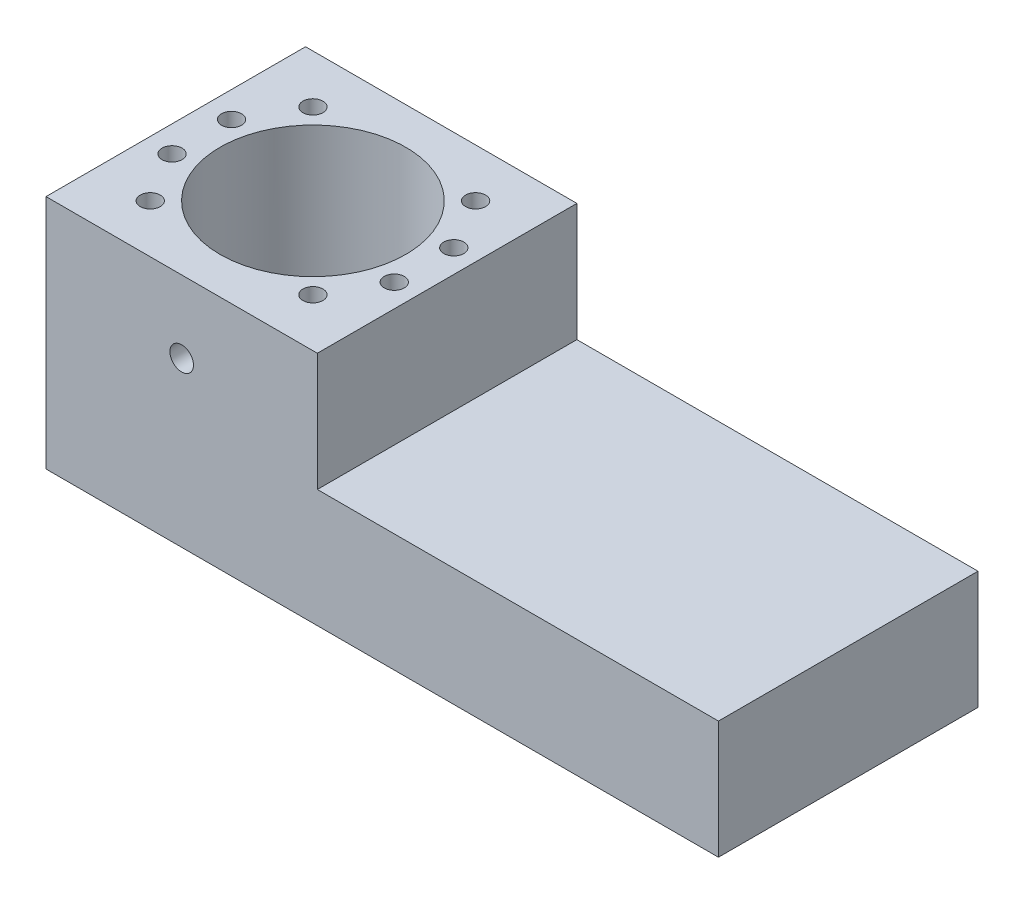
SolidWorks part; units mm, degrees
ref_plane "前视基准面" through (0, 0, 0) normal (0, 0, 1) x (1, 0, 0)
ref_plane "上视基准面" through (0, 0, 0) normal (0, 1, 0) x (1, 0, 0)
ref_plane "右视基准面" through (0, 0, 0) normal (1, 0, 0) x (0, 0, -1)
other "Configuration Table"
sketch "草图2" plane through (0, 0, 0) normal (0, 1, 0) x (1, 0, 0)
  line L1 (0, 0) -> (228, 0)
  line L2 (0, 0) -> (0, 88)
  line L3 (0, 88) -> (228, 88)
  line L4 (228, 0) -> (228, 88)
  dimension "D1" = 228
  dimension "D2" = 88
extrude "凸台-拉伸1" add sketch "草图2" along normal blind 40
sketch "草图3" plane through (0, 40, 0) normal (0, 1, 0) x (1, 0, 0)
  line L0 (0, 0) -> (228, 0) construction
  line L1 (0, 88) -> (92, 88)
  line L2 (0, 88) -> (0, 0)
  line L3 (0, 0) -> (92, 0)
  line L4 (92, 88) -> (92, 0)
  dimension "D1" = 92
extrude "凸台-拉伸2" add sketch "草图3" along normal blind 40
sketch "草图4" plane through (0, 80, 0) normal (0, 1, 0) x (1, 0, 0)
  line L0 (0, 88) -> (0, 0) construction
  line L1 (92, 88) -> (0, 88) construction
  circle A0 centre (46.5, 44) radius 31.5
  dimension "D3" = 63
  dimension "D1" = 46.5
  dimension "D2" = 44
extrude "切除-拉伸1" cut sketch "草图4" against normal up to next
sketch "草图5" plane through (0, 80, 0) normal (0, 1, 0) x (1, 0, 0)
  line L0 (0, 44) -> (92, 44) construction
  line L1 (46.5, 44) -> (74.0772, 16.4228) construction
  line L2 (46.5, 44) -> (84.1711, 33.9061) construction
  line L3 (46.5, 83) -> (46.5, 5) construction
  line L4 (8.8289, 54.0939) -> (46.5, 44) construction
  line L5 (46.5, 44) -> (8.8289, 33.9061) construction
  line L6 (46.5, 44) -> (18.9228, 71.5772) construction
  line L7 (46.5, 44) -> (18.9228, 16.4228) construction
  line L8 (84.1711, 54.0939) -> (46.5, 44) construction
  line L9 (46.5, 44) -> (74.0772, 71.5772) construction
  circle A0 centre (46.5, 44) radius 39 construction
  point P6 (8.8289, 54.0939)
  point P7 (18.9228, 16.4228)
  point P8 (8.8289, 33.9061)
  point P10 (74.0772, 16.4228)
  point P11 (18.9228, 71.5772)
  point P12 (84.1711, 33.9061)
  point P13 (84.1711, 54.0939)
  point P14 (74.0772, 71.5772)
  point P35 (46.5, 83)
  point P39 (18.9228, 71.5772)
  point P41 (8.8289, 54.0939)
  point P43 (8.8289, 33.9061)
  point P45 (18.9228, 16.4228)
  point P47 (74.0772, 16.4228)
  point P49 (84.1711, 54.0939)
  point P51 (84.1711, 33.9061)
  point P68 (74.0772, 71.5772)
  dimension "D1" = 78
  dimension "D2" = 30
  dimension "D3" = 15
  dimension "D4" = 45
hole_wizard "M8 螺纹孔3" positions "草图5" profile "草图6" tap size "M8" standard "GB"
sketch "草图6" plane through (74.0772, 80, -71.5772) normal (1, 0, 0) x (0, 0, 1)
  line L0 (0, 0) -> (0, 32.0429)
  line L1 (0, 32.0429) -> (3.4, 30)
  line L2 (3.4, 30) -> (3.4, 0)
  line L5 (3.4, 0) -> (0, 0)
  line L10 (0, 32.0429) -> (-3.4, 30) construction
  line L11 (0, -6.35) -> (0, 107.95) construction
  dimension "螺纹孔钻头直径" = 6.8
  dimension "螺纹孔钻头深度" = 30
  dimension "导头角度" = 118
cosmetic thread "孔螺蚊线1" parameters "D1"=16, "D2"=8
cosmetic thread "孔螺蚊线2" parameters "D1"=16, "D2"=8
cosmetic thread "孔螺蚊线3" parameters "D1"=16, "D2"=8
cosmetic thread "孔螺蚊线4" parameters "D1"=16, "D2"=8
cosmetic thread "孔螺蚊线5" parameters "D1"=16, "D2"=8
cosmetic thread "孔螺蚊线6" parameters "D1"=16, "D2"=8
cosmetic thread "孔螺蚊线7" parameters "D1"=16, "D2"=8
cosmetic thread "孔螺蚊线8" parameters "D1"=16, "D2"=8
sketch "草图7" plane through (0, 40, 0) normal (0, 1, 0) x (1, 0, 0)
  line L0 (0, 44) -> (247.0799, 44) construction
  line L1 (0, 88) -> (0, 0) construction
  line L2 (-200000, 44) -> (200092, 44) construction
  line L4 (228, 88) -> (92, 88) construction
  circle A0 centre (139.5, 78) radius 5.5
  circle A1 centre (176.5, 78) radius 5.5
  circle A2 centre (213.5, 78) radius 5.5
  circle A3 centre (176.5, 44) radius 5.5
  circle A4 centre (213.5, 44) radius 5.5
  circle A5 centre (176.5, 10) radius 5.5
  circle A6 centre (213.5, 10) radius 5.5
  circle A7 centre (139.5, 44) radius 5.5
  circle A8 centre (139.5, 10) radius 5.5
  dimension "D2" = 11
  dimension "D1" = 93
  dimension "D5" = 10
  dimension "D6" = 37
  dimension "D3" = 3
  dimension "D4" = 3
extrude "切除-拉伸2" [suppressed] cut sketch "草图7" against normal up to next
sketch "草图8" plane through (0, 0, 0) normal (0, 0, 1) x (1, 0, 0)
  circle A0 centre (46, 55.4965) radius 4
  dimension "D1" = 8
extrude "切除-拉伸3" cut sketch "草图8" against normal up to next
